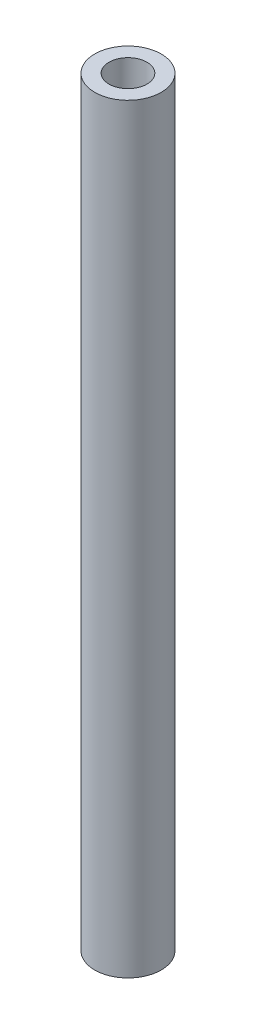
SolidWorks part; units mm, degrees
ref_plane "Front Plane" through (0, 0, 0) normal (0, 0, 1) x (1, 0, 0)
ref_plane "Top Plane" through (0, 0, 0) normal (0, 1, 0) x (1, 0, 0)
ref_plane "Right Plane" through (0, 0, 0) normal (1, 0, 0) x (0, 0, -1)
sketch "Sketch1" plane through (0, 0, 0) normal (0, 1, 0) x (1, 0, 0)
  circle A0 centre (0, 0) radius 1
  circle A1 centre (0, 0) radius 1.75
  dimension "D1" = 2
  dimension "D2" = 3.5
extrude "Boss-Extrude1" add sketch "Sketch1" along normal blind 40
